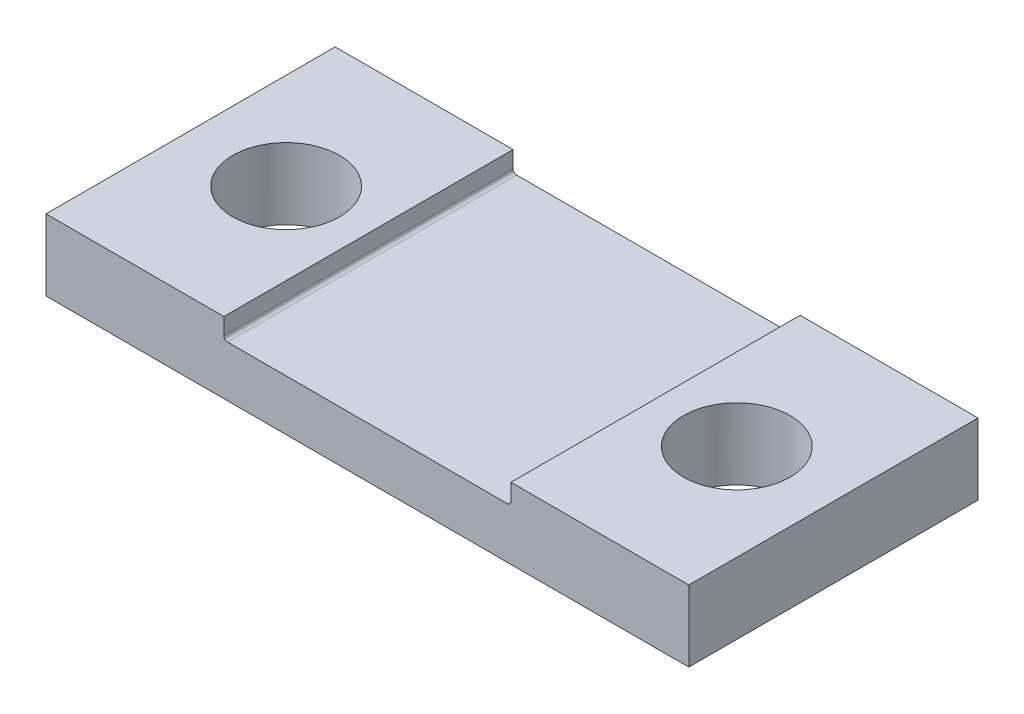
SolidWorks part; units mm, degrees
ref_plane "Front Plane" through (0, 0, 0) normal (0, 0, 1) x (1, 0, 0)
ref_plane "Top Plane" through (0, 0, 0) normal (0, 1, 0) x (1, 0, 0)
ref_plane "Right Plane" through (0, 0, 0) normal (1, 0, 0) x (0, 0, -1)
sketch "Sketch1" plane through (0, 0, 0) normal (0, 0, 1) x (1, 0, 0)
  line L0 (-9.035, 0) -> (-9.035, 2)
  line L1 (-9.035, 2) -> (-4.035, 2)
  line L2 (-4.035, 2) -> (-4.035, 1.53)
  line L3 (-3.935, 1.43) -> (3.935, 1.43)
  line L4 (4.035, 1.53) -> (4.035, 2)
  line L5 (4.035, 2) -> (9.035, 2)
  line L6 (9.035, 2) -> (9.035, 0)
  line L7 (9.035, 0) -> (-9.035, 0)
  arc A0 (3.935, 1.43) -> (4.035, 1.53) centre (3.935, 1.53) ccw
  arc A1 (-4.035, 1.53) -> (-3.935, 1.43) centre (-3.935, 1.53) ccw
  point P12 (0, 0)
  point P16 (0, 1.43)
  point P19 (4.035, 1.43)
  point P22 (-4.035, 1.43)
  dimension "D5" = 0.1
  dimension "D1" = 2
  dimension "D2" = 1.43
  dimension "D3" = 18.07
  dimension "D4" = 5
extrude "Boss-Extrude1" add sketch "Sketch1" along normal blind 8.13
hole_wizard "Ø3.0mm Dowel Hole1" positions "Sketch2" profile "Sketch3" hole size "Ø3.0" standard "ISO"
sketch "Sketch2" plane through (0, 2, 0) normal (0, 1, 0) x (1, 0, 0)
  line L1 (9.035, -8.13) -> (4.035, -8.13) construction
  line L2 (-4.035, -8.13) -> (-9.035, -8.13) construction
  line L3 (-9.035, -8.13) -> (-9.035, 0) construction
  line L4 (9.035, -8.13) -> (9.035, 0) construction
  point P0 (6.335, -4.08)
  point P2 (-6.335, -4.08)
  dimension "D1" = 4.05
  dimension "D2" = 4.05
  dimension "D3" = 2.7
  dimension "D4" = 2.7
sketch "Sketch3" plane through (6.335, 2, 4.08) normal (1, 0, 0) x (0, 0, 1)
  line L0 (0, 0) -> (0, 35.9013)
  line L1 (0, 35.9013) -> (1.5, 35)
  line L2 (1.5, 35) -> (1.5, 0)
  line L5 (1.5, 0) -> (0, 0)
  line L10 (0, 35.9013) -> (-1.5, 35) construction
  line L11 (0, -6.35) -> (0, 107.95) construction
  dimension "Hole Dia." = 3
  dimension "Hole Depth" = 35
  dimension "Drill Angle" = 118
